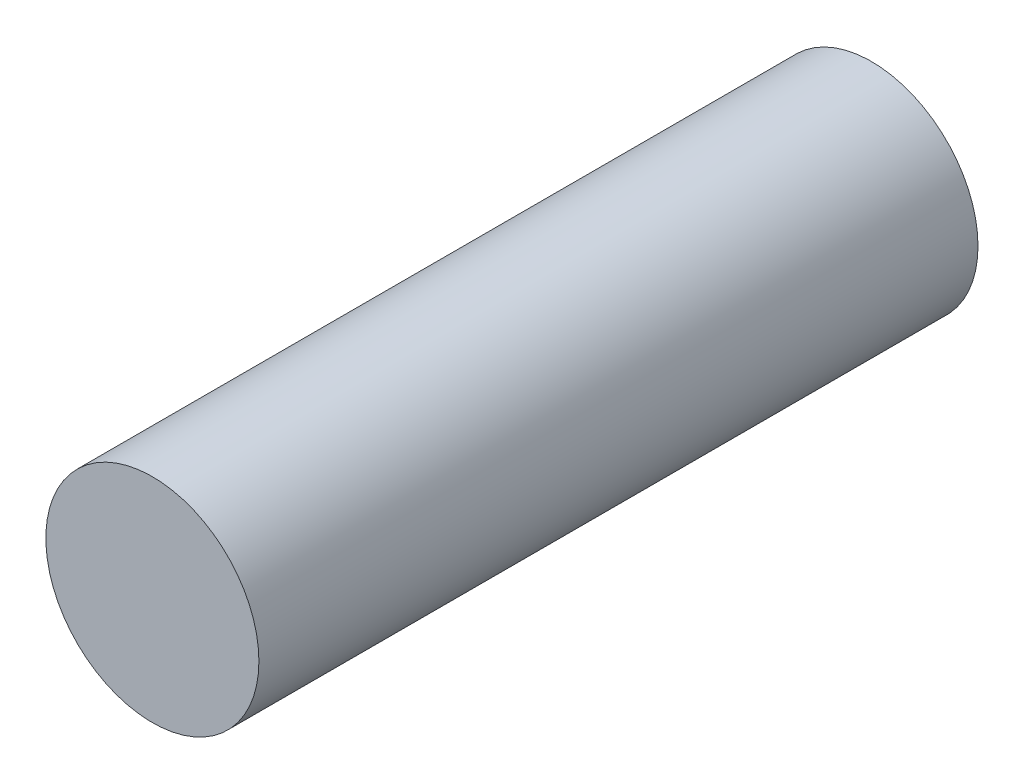
SolidWorks part; units mm, degrees
ref_plane "前视基准面" through (0, 0, 0) normal (0, 0, 1) x (1, 0, 0)
ref_plane "上视基准面" through (0, 0, 0) normal (0, 1, 0) x (1, 0, 0)
ref_plane "右视基准面" through (0, 0, 0) normal (1, 0, 0) x (0, 0, -1)
other "Configuration Table"
sketch "草图1" plane through (0, 0, 0) normal (0, 0, 1) x (1, 0, 0)
  circle A0 centre (0, 0) radius 2
  dimension "D1" = 4
extrude "凸台-拉伸1" add sketch "草图1" along normal blind 13.5
